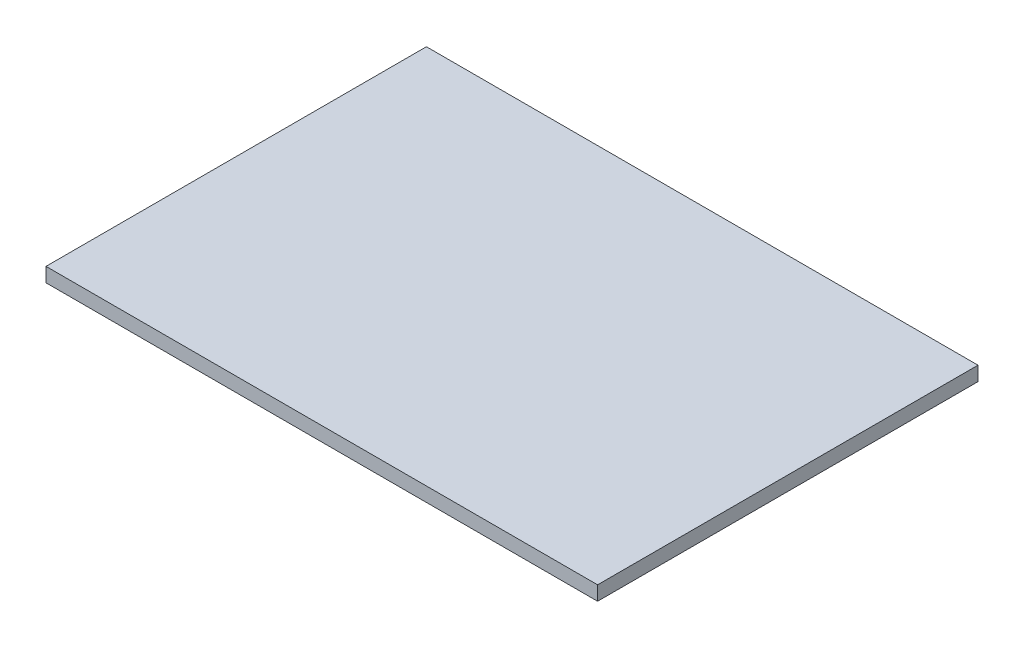
SolidWorks part; units mm, degrees
ref_plane "Front Plane" through (0, 0, 0) normal (0, 0, 1) x (1, 0, 0)
ref_plane "Top Plane" through (0, 0, 0) normal (0, 1, 0) x (1, 0, 0)
ref_plane "Right Plane" through (0, 0, 0) normal (1, 0, 0) x (0, 0, -1)
sketch "Sketch1" plane through (0, 0, 0) normal (0, 1, 0) x (1, 0, 0)
  line L1 (-98.5616, 82.4003) -> (17.4384, 82.4003)
  line L2 (-98.5616, 82.4003) -> (-98.5616, 2.4003)
  line L3 (-98.5616, 2.4003) -> (17.4384, 2.4003)
  line L4 (17.4384, 82.4003) -> (17.4384, 2.4003)
  dimension "D1" = 116
  dimension "D2" = 80
extrude "Boss-Extrude1" add sketch "Sketch1" along normal blind 3
